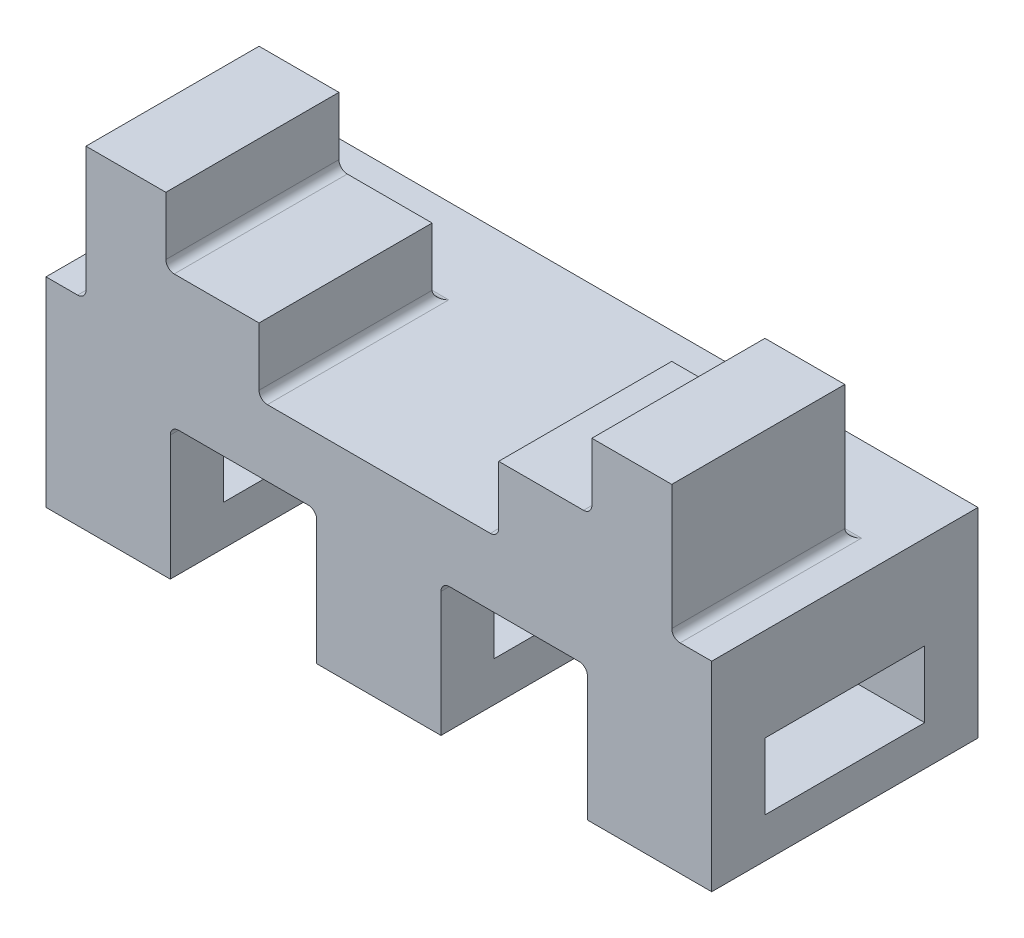
SolidWorks part; units mm, degrees
ref_plane "Front Plane" through (0, 0, 0) normal (0, 0, 1) x (1, 0, 0)
ref_plane "Top Plane" through (0, 0, 0) normal (0, 1, 0) x (1, 0, 0)
ref_plane "Right Plane" through (0, 0, 0) normal (1, 0, 0) x (0, 0, -1)
sketch "Sketch1" plane through (0, 0, 0) normal (0, 0, 1) x (1, 0, 0)
  line L0 (-63.5, 0) -> (-63.5, 38.1)
  line L1 (-63.5, 38.1) -> (63.5, 38.1)
  line L2 (63.5, 38.1) -> (63.5, 0)
  line L3 (63.5, 0) -> (39.7933, 0)
  line L4 (39.7933, 0) -> (39.7933, 25.4)
  line L5 (39.7933, 25.4) -> (11.8533, 25.4)
  line L6 (11.8533, 25.4) -> (11.8533, 0)
  line L7 (11.8533, 0) -> (-11.8533, 0)
  line L8 (-11.8533, 0) -> (-11.8533, 25.4)
  line L9 (-11.8533, 25.4) -> (-39.7933, 25.4)
  line L10 (-39.7933, 25.4) -> (-39.7933, 0)
  line L11 (-39.7933, 0) -> (-63.5, 0)
  line L12 (0, 0) -> (0, 71.5057) construction
  dimension "D1" = 127
  dimension "D2" = 27.94
  dimension "D3" = 25.4
  dimension "D4" = 38.1
extrude "Boss-Extrude1" add sketch "Sketch1" along normal blind 50.8
sketch "Sketch2" plane through (0, 0, 50.8) normal (0, 0, 1) x (1, 0, 0)
  line L0 (55.8767, 38.1) -> (55.8767, 63.5)
  line L1 (63.5, 38.1) -> (-63.5, 38.1) construction
  line L2 (55.8767, 63.5) -> (40.6367, 63.5)
  line L3 (40.6367, 63.5) -> (40.6367, 50.8)
  line L4 (40.6367, 50.8) -> (22.8567, 50.8)
  line L5 (22.8567, 50.8) -> (22.8567, 38.1)
  line L6 (22.8567, 38.1) -> (55.8767, 38.1)
  line L14 (0, 0) -> (0, 38.1) construction
  dimension "D1" = 63.5
  dimension "D2" = 12.7
  dimension "D3" = 15.24
  dimension "D4" = 33.02
extrude "Boss-Extrude2" add sketch "Sketch2" against normal blind 33.02
mirror "Mirror1" about plane through (0, 0, 0) normal (1, 0, 0) of "Boss-Extrude2"
fillet "Fillet2" radius 1.5875 12 edges at (-39.3667, 38.1, 17.78) (-22.8567, 38.1, 34.29) (-40.6367, 50.8, 34.29) (-55.8767, 38.1, 34.29) (39.3667, 38.1, 17.78) (55.8767, 38.1, 34.29) (22.8567, 38.1, 34.29) (39.7933, 25.4, 25.4) (11.8533, 25.4, 25.4) (-11.8533, 25.4, 25.4) (-39.7933, 25.4, 25.4) (40.6367, 50.8, 34.29)
sketch "Sketch3" plane through (-63.5, 0, 0) normal (-1, 0, 0) x (0, 0, 1)
  line L0 (50.8, 38.1) -> (50.8, 0) construction
  line L1 (10.16, 20.32) -> (40.64, 20.32)
  line L2 (10.16, 20.32) -> (10.16, 7.62)
  line L3 (10.16, 7.62) -> (40.64, 7.62)
  line L4 (40.64, 20.32) -> (40.64, 7.62)
  line L5 (10.16, 20.32) -> (40.64, 7.62) construction
  line L6 (10.16, 7.62) -> (40.64, 20.32) construction
  line L7 (50.8, 0) -> (0, 0) construction
  point P0 (25.4, 13.97)
  dimension "D1" = 30.48
  dimension "D2" = 10.16
  dimension "D3" = 12.7
  dimension "D4" = 7.62
extrude "Cut-Extrude1" cut sketch "Sketch3" against normal up to surface (127 mm away) up to face at (63.5, 19.05, 25.4)
